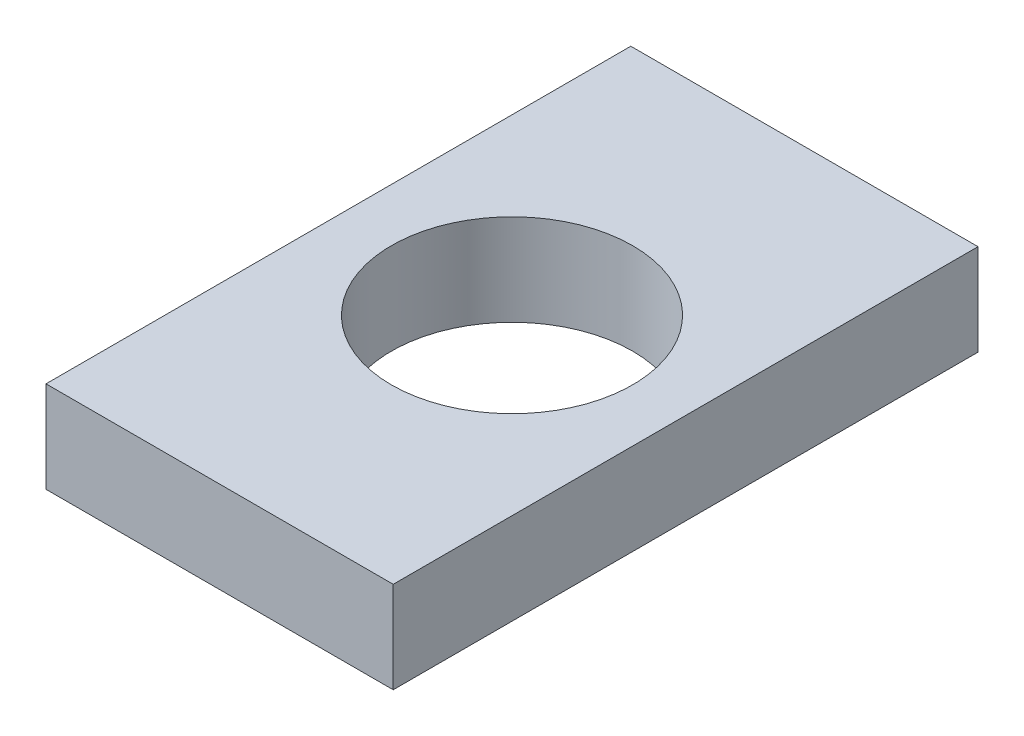
SolidWorks part; units mm, degrees
ref_plane "Front Plane" through (0, 0, 0) normal (0, 0, 1) x (1, 0, 0)
ref_plane "Top Plane" through (0, 0, 0) normal (0, 1, 0) x (1, 0, 0)
ref_plane "Right Plane" through (0, 0, 0) normal (1, 0, 0) x (0, 0, -1)
sketch "Sketch1" plane through (0, 0, 0) normal (0, 1, 0) x (1, 0, 0)
  line L1 (0, 0) -> (4.75, 0)
  line L2 (0, 0) -> (0, 8)
  line L3 (0, 8) -> (4.75, 8)
  line L4 (4.75, 0) -> (4.75, 8)
  dimension "D1" = 8
  dimension "D2" = 4.75
extrude "Boss-Extrude1" add sketch "Sketch1" along normal blind 1.25
hole_wizard "M4x0.7 Tapped Hole1" positions "Sketch2" profile "Sketch3" tap size "M4x0.7" standard "ANSI Metric" end condition through all
sketch "Sketch2" plane through (0, 1.25, 0) normal (0, 1, 0) x (1, 0, 0)
  line L0 (2.375, 8) -> (2.375, 0) construction
  line L1 (4.75, 8) -> (0, 8) construction
  line L2 (0, 0) -> (4.75, 0) construction
  point P0 (2.375, 4)
  point P12 (2.375, 4)
sketch "Sketch3" plane through (2.375, 1.25, -4) normal (1, 0, 0) x (0, 0, 1)
  line L0 (0, 0) -> (0, 1.25)
  line L1 (0, 1.25) -> (1.65, 1.25)
  line L2 (1.65, 1.25) -> (1.65, 0)
  line L5 (1.65, 0) -> (0, 0)
  line L11 (0, -6.35) -> (0, 107.95) construction
  dimension "Thru Tap Drill Dia." = 3.3
  dimension "Thru Tap Drill Depth" = 1.25
cosmetic thread "Hole Thread1"
